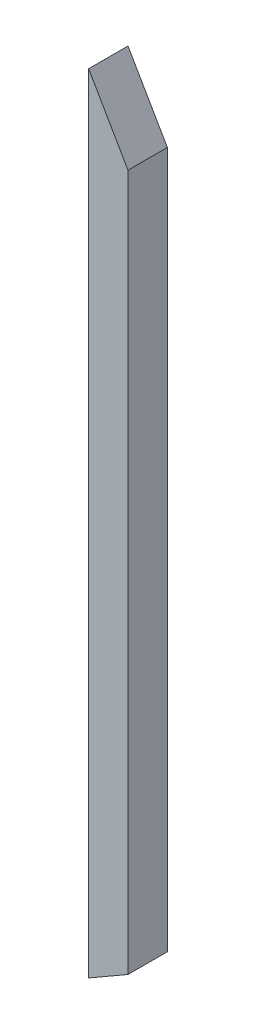
SolidWorks part; units mm, degrees
ref_plane "前视基准面" through (0, 0, 0) normal (0, 0, 1) x (1, 0, 0)
ref_plane "上视基准面" through (0, 0, 0) normal (0, 1, 0) x (1, 0, 0)
ref_plane "右视基准面" through (0, 0, 0) normal (1, 0, 0) x (0, 0, -1)
sketch "草图1" plane through (0, 0, 0) normal (0, 1, 0) x (1, 0, 0)
  line L1 (0, 0) -> (30, 0)
  line L2 (0, 0) -> (0, -30)
  line L3 (0, -30) -> (30, -30)
  line L4 (30, 0) -> (30, -30)
  dimension "D1" = 30
  dimension "D2" = 30
extrude "凸台-拉伸1" add sketch "草图1" along normal blind 600
sketch "草图2" plane through (0, 0, 30) normal (0, 0, 1) x (1, 0, 0)
  line L0 (0, 0) -> (30, 8.0385)
  line L1 (0, 0) -> (30, 0) construction
  line L2 (30, 600) -> (30, 0) construction
  line L3 (30, 8.0385) -> (30, 0)
  line L4 (30, 0) -> (0, 0)
  dimension "D1" = 15
extrude "切除-拉伸1" cut sketch "草图2" against normal up to next
sketch "草图3" plane through (0, 0, 0) normal (0, 0, -1) x (-1, 0, 0)
  line L0 (0, 600) -> (-30, 600)
  line L2 (0, 600) -> (-30, 488.0385)
  line L3 (-30, 600) -> (-30, 8.0385) construction
  line L4 (-30, 600) -> (-30, 488.0385)
extrude "切除-拉伸2" cut sketch "草图3" against normal up to next
sketch "草图5" plane through (0, 0, 0) normal (0, 0, -1) x (-1, 0, 0)
  line L0 (-30, 17.3205) -> (-30, 8.0385)
  line L1 (0, 0) -> (-30, 17.3205)
  line L2 (-30, 488.0385) -> (-30, 8.0385) construction
  line L3 (-30, 8.0385) -> (0, 0)
extrude "切除-拉伸3" cut sketch "草图5" against normal through all
sketch "草图6" plane through (0, 0, 0) normal (0, 0, -1) x (-1, 0, 0)
  line L0 (-30, 488.0385) -> (0, 600)
  line L1 (0, 600) -> (-30, 548.0385)
  line L2 (-30, 548.0385) -> (-30, 488.0385)
  line L3 (-30, 488.0385) -> (-30, 17.3205) construction
  dimension "D1" = 15
  dimension "D2" = 180
extrude "凸台-拉伸2" add sketch "草图6" against normal up to surface (30 mm away) up to face at (15, 276.3397, 30)
